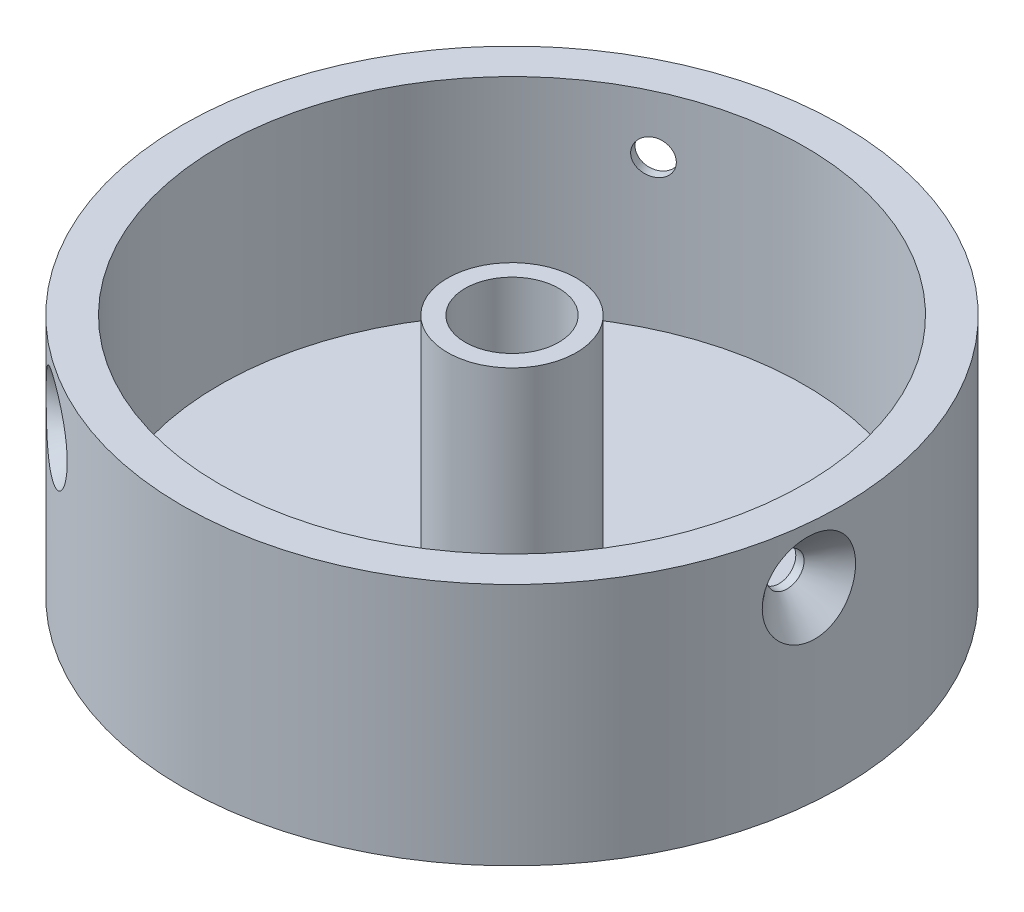
SolidWorks part; units mm, degrees
ref_plane "Front Plane" through (0, 0, 0) normal (0, 0, 1) x (1, 0, 0)
ref_plane "Top Plane" through (0, 0, 0) normal (0, 1, 0) x (1, 0, 0)
ref_plane "Right Plane" through (0, 0, 0) normal (1, 0, 0) x (0, 0, -1)
sketch "Sketch1" plane through (0, 0, 0) normal (0, 1, 0) x (1, 0, 0)
  circle A0 centre (0, 0) radius 23
  dimension "D1" = 46
extrude "Boss-Extrude1" add sketch "Sketch1" along normal blind 17
shell "Shell1" thickness 2.6
sketch "Sketch2" plane through (0, 0, 0) normal (0, -1, 0) x (1, 0, 0)
  line L0 (0, -23) -> (0, 5)
  line L1 (6, -18) -> (-6, -18)
  line L2 (-6, -18) -> (-6, 5)
  line L3 (-6, 5) -> (6, 5)
  line L4 (6, -18) -> (6, 5)
  circle A0 centre (0, 0) radius 23 construction
  point P9 (0, -18)
  dimension "D1" = 28
  dimension "D2" = 23
  dimension "D3" = 6
extrude "Boss-Extrude2" [suppressed] add sketch "Sketch2" along normal blind 6 contours L3 L2 L1 L0 | L1 L4 L3 L0
sketch "Sketch3" [suppressed] plane through (0, 0, -18) normal (0, 0, -1) x (-1, 0, 0)
  line L0 (-6, -3) -> (-4, -3)
  line L2 (-6, -6) -> (-6, 0) construction
  line L3 (-4, -3) -> (-4, 0)
  line L4 (-6, 0) -> (6, 0) construction
  line L5 (-4, 0) -> (-6, 0)
  line L6 (-6, 0) -> (-6, -3)
  line L7 (0, -6) -> (0, 0) construction
  line L8 (-6, -6) -> (6, -6) construction
  line L9 (4, 0) -> (6, 0)
  line L10 (4, -3) -> (4, 0)
  line L11 (6, -3) -> (4, -3)
  line L12 (6, 0) -> (6, -3)
  dimension "D1" = 2
extrude "Cut-Extrude1" [suppressed] cut sketch "Sketch3" against normal through all
sketch "Sketch4" plane through (0, 2.6, 0) normal (0, 1, 0) x (1, 0, 0)
  circle A0 centre (0, 0) radius 4.5
  dimension "D1" = 9
extrude "Boss-Extrude3" add sketch "Sketch4" along normal up to surface (14.4 mm away) up to face at (0, 17, 20.4)
sketch "Sketch5" plane through (0, 17, 0) normal (0, 1, 0) x (1, 0, 0)
  circle A0 centre (0, 0) radius 3.265
  dimension "D1" = 6.53
extrude "Cut-Extrude2" cut sketch "Sketch5" against normal through all
ref_plane "Plane1" [suppressed] through (0, 0, 5) normal (0, 0, 1) x (1, 0, 0)
sketch "Sketch7" [suppressed] plane through (0, 0, 5) normal (0, 0, 1) x (1, 0, 0)
  line L0 (-1.91, -4.3) -> (-1.91, -1.7)
  line L1 (-1.91, -4.3) -> (1.91, -4.3)
  line L2 (-1.91, -1.7) -> (1.91, -1.7)
  line L3 (1.91, -4.3) -> (1.91, -1.7)
  line L4 (0, -6) -> (0, 0) construction
  line L5 (-1.91, -3) -> (1.91, -3) construction
  line L6 (-6, -6) -> (6, -6) construction
  point P8 (0, -3)
  point P10 (0, -3)
  dimension "D1" = 3.82
  dimension "D2" = 2.6
extrude "Cut-Extrude3" [suppressed] cut sketch "Sketch7" against normal blind 1.71
ref_plane "Plane2" [suppressed] through (0, -3, 0) normal (0, -1, 0) x (-1, 0, 0)
sketch "Sketch8" [suppressed] plane through (0, -3, 0) normal (0, -1, 0) x (-1, 0, 0)
  line L0 (-4, -1.3082) -> (-4, -2.5)
  line L1 (-4, -1.3082) -> (4.0117, -1.3082)
  line L2 (-3.9936, -3.2831) -> (4.0181, -3.2831)
  line L3 (4.0117, -1.3082) -> (4.0117, -2.5)
  line L4 (-4, -5) -> (-4, 18) construction
  line L7 (-3.9936, -3.2831) -> (-4, -2.5)
  line L8 (4.0181, -3.2831) -> (4.0117, -2.5)
extrude "Boss-Extrude4" [suppressed] add sketch "Sketch8" against normal blind 3
hole_wizard "CSK SLOT for M2 Countersunk Flat Head Screw1" positions "3DSketch1" profile "Sketch9" size "M2" standard "ISO" slot yes
sketch3d "3DSketch1"
  line L0 (22.9111, 13, 2.0208) -> (22.9111, 0, 2.0208) construction
  circle A0 centre (0, 0, 0) radius 23 construction
  point P0 (22.9111, 13, 2.0208)
  point P5 (0, 23, 0)
  dimension "D1" = 13
sketch "Sketch9" plane through (22.9111, 13, 2.0208) normal (0, 1, 0) x (0.0879, 0, -0.9961)
  line L0 (0, 0) -> (0, 5.721)
  line L1 (0, 5.721) -> (1.2, 5)
  line L2 (1.2, 5) -> (1.2, 2)
  line L3 (1.2, 2) -> (3.2, 0)
  line L5 (3.2, 0) -> (0, 0)
  line L6 (-1.2, 2) -> (-3.2, 0) construction
  line L10 (0, 5.721) -> (-1.2, 5) construction
  line L11 (0, -6.35) -> (0, 107.95) construction
  dimension "Hole Dia." = 2.4
  dimension "Hole Depth" = 5
  dimension "Near C'Sink Dia." = 6.4
  dimension "Near C'Sink Angle" = 90
  dimension "Drill Angle" = 118
pattern_circular "CirPattern1" count 3 over 360 about axis through (0, 17, 0) along (0, -1, 0) of "CSK SLOT for M2 Countersunk Flat Head Screw1"
sketch "Sketch10" [suppressed] plane through (0, 0, 3.29) normal (0, 0, 1) x (1, 0, 0)
  line L0 (-1.91, -3) -> (-1.55, -3) construction
  line L1 (-1.91, -1.7) -> (-1.91, -4.3) construction
  line L2 (1.91, -4.3) -> (1.91, -1.7) construction
  line L4 (1.55, -3.9) -> (-1.55, -3.9)
  line L5 (1.55, -3.9) -> (1.55, -1.7)
  line L6 (1.55, -1.7) -> (-1.55, -1.7)
  line L7 (-1.55, -3.9) -> (-1.55, -1.7)
  line L8 (1.91, -1.7) -> (-1.91, -1.7) construction
  line L11 (1.55, -3) -> (1.91, -3) construction
  point P6 (0, -3)
  point P7 (0, -3)
  dimension "D1" = 3.1
extrude "Cut-Extrude4" [suppressed] cut sketch "Sketch10" against normal blind 3
sketch "Sketch11" [suppressed] plane through (0, -3.9, 0) normal (0, 1, 0) x (1, 0, 0)
  line L0 (1.55, -3.29) -> (-1.55, -3.29)
  line L1 (1.55, -3.29) -> (1.55, -2.102)
  line L2 (-1.55, -3.29) -> (-1.55, -2.102)
  line L3 (1.55, -2.102) -> (-1.55, -2.102)
extrude "Boss-Extrude6" [suppressed] add sketch "Sketch11" against normal up to next
fillet "Fillet1" [suppressed] radius 2
sketch "Sketch14" plane through (0, 2.6, 0) normal (0, 1, 0) x (1, 0, 0)
  circle A0 centre (3.5648, -10.4064) radius 3
  point P3 (0, 0)
  dimension "D1" = 6
extrude "Boss-Extrude7" add sketch "Sketch14" along normal blind 3
hole_wizard "M1.6 Tapped Hole1" positions "Sketch12" profile "Sketch13" tap size "M1.6" standard "ISO" end condition through all
sketch "Sketch12" plane through (0, 0, 0) normal (0, -1, 0) x (-1, 0, 0)
  line L4 (0, 0) -> (-23, 0)
  line L6 (0, 0) -> (13.1526, -18.8682)
  line L8 (0, 0) -> (-7.4537, -21.7587)
  circle A1 centre (0, 0) radius 23 construction
  point P0 (-3.5648, -10.4064)
  point P33 (0, 0)
  dimension "D1" = 12
sketch "Sketch13" plane through (3.5648, 0, 10.4064) normal (1, 0, 0) x (0, 0, -1)
  line L0 (0, 0) -> (0, 17)
  line L1 (0, 17) -> (0.625, 17)
  line L2 (0.625, 17) -> (0.625, 0.2)
  line L3 (0.625, 0.2) -> (0.825, 0)
  line L5 (0.825, 0) -> (0, 0)
  line L6 (-0.625, 0.2) -> (-0.825, 0) construction
  line L11 (0, -6.35) -> (0, 107.95) construction
  dimension "Thru Tap Drill Dia." = 1.25
  dimension "Thru Tap Drill Depth" = 17
  dimension "Near C'Sink Dia." = 1.65
  dimension "Near C'Sink Angle" = 90
cosmetic thread "Hole Thread1" parameters "D2"=1.6
